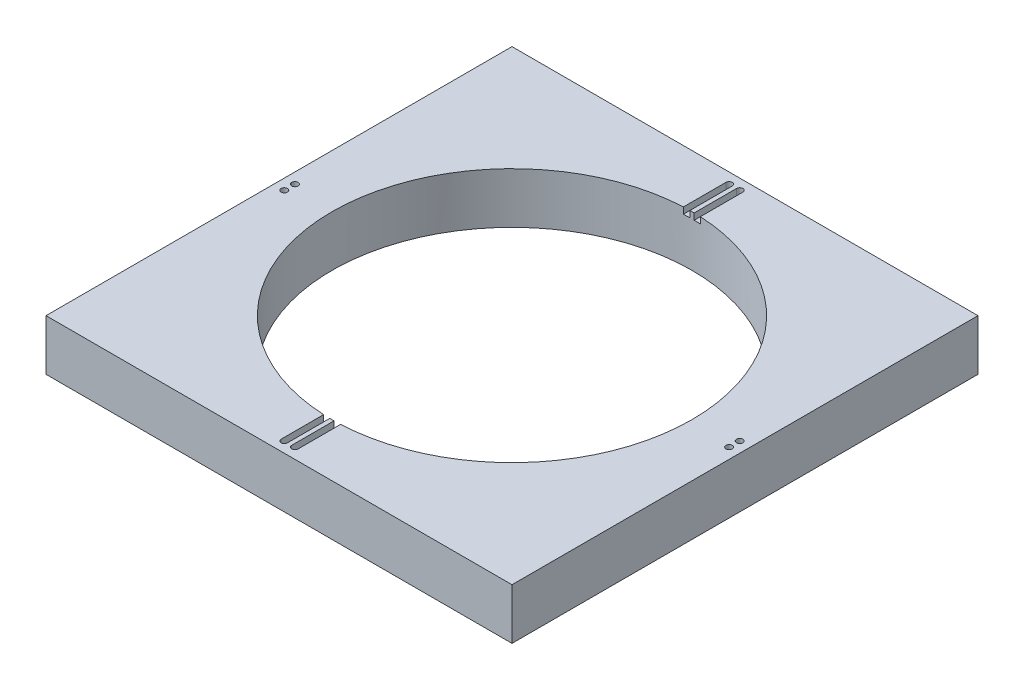
SolidWorks part; units mm, degrees
material "Oak"
ref_plane "Front Plane" through (0, 0, 0) normal (0, 0, 1) x (1, 0, 0)
ref_plane "Top Plane" through (0, 0, 0) normal (0, 1, 0) x (1, 0, 0)
ref_plane "Right Plane" through (0, 0, 0) normal (1, 0, 0) x (0, 0, -1)
sketch "Sketch1" plane through (0, 0, 0) normal (0, 1, 0) x (1, 0, 0)
  line L0 (-105, 2.5) -> (105, 2.5) construction
  line L1 (-110, -110) -> (110, -110)
  line L2 (-110, -110) -> (-110, 110)
  line L3 (-110, 110) -> (110, 110)
  line L4 (110, -110) -> (110, 110)
  line L5 (-110, -110) -> (110, 110) construction
  line L6 (-110, 110) -> (110, -110) construction
  line L7 (-105, -105) -> (105, -105) construction
  line L8 (-105, -105) -> (-105, 105) construction
  line L9 (-105, 105) -> (105, 105) construction
  line L10 (105, -105) -> (105, 105) construction
  line L11 (-105, -105) -> (105, 105) construction
  line L12 (-105, 105) -> (105, -105) construction
  line L13 (-105, -2.5) -> (105, -2.5) construction
  line L14 (-2.5, 105) -> (-2.5, -105) construction
  line L15 (2.5, -105) -> (2.5, 105) construction
  circle A0 centre (0, 0) radius 85
  circle A1 centre (-105, 2.5) radius 1.5
  circle A2 centre (-105, -2.5) radius 1.5
  circle A3 centre (105, 2.5) radius 1.5
  circle A4 centre (105, -2.5) radius 1.5
  circle A5 centre (-2.5, -105) radius 1.5
  circle A6 centre (2.5, -105) radius 1.5
  circle A7 centre (-2.5, 105) radius 1.5
  circle A8 centre (2.5, 105) radius 1.5
  point P19 (-105, 0)
  point P20 (0, -105)
  dimension "D2" = 170
  dimension "D4" = 3
  dimension "D1" = 220
  dimension "D3" = 210
  dimension "D5" = 2.5
  dimension "D6" = 2.5
  dimension "D7" = 2.5
  dimension "D8" = 2.5
extrude "Boss-Extrude1" add sketch "Sketch1" along normal blind 24
sketch "Sketch2" plane through (0, 24, 0) normal (0, 1, 0) x (1, 0, 0)
  line L0 (0, 110) -> (0, -110) construction
  line L1 (110, 110) -> (-110, 110) construction
  line L2 (-110, -110) -> (110, -110) construction
  line L5 (-110, 0) -> (110, 0) construction
  line L6 (-110, 110) -> (-110, -110) construction
  line L7 (110, -110) -> (110, 110) construction
  line L10 (2.5, 105) -> (2.5, -105) construction
  line L11 (4, 105) -> (4, -105)
  line L12 (1, 105) -> (1, -105)
  line L13 (-2.5, 105) -> (-2.5, -105) construction
  line L14 (-1, 105) -> (-1, -105)
  line L15 (-4, 105) -> (-4, -105)
  arc A4 (4, 105) -> (1, 105) centre (2.5, 105) ccw
  arc A5 (1, -105) -> (4, -105) centre (2.5, -105) ccw
  circle A6 centre (2.5, -105) radius 1.5 construction
  arc A7 (-1, 105) -> (-4, 105) centre (-2.5, 105) ccw
  arc A8 (-4, -105) -> (-1, -105) centre (-2.5, -105) ccw
  circle A9 centre (-2.5, -105) radius 1.5 construction
  point P8 (2.5, 0)
  point P23 (-2.5, 0)
extrude "Cut-Extrude1" cut sketch "Sketch2" against normal blind 3
equation "\"D7@Sketch1\"=\"D5@Sketch1\""
equation "\"D8@Sketch1\"=\"D7@Sketch1\""
